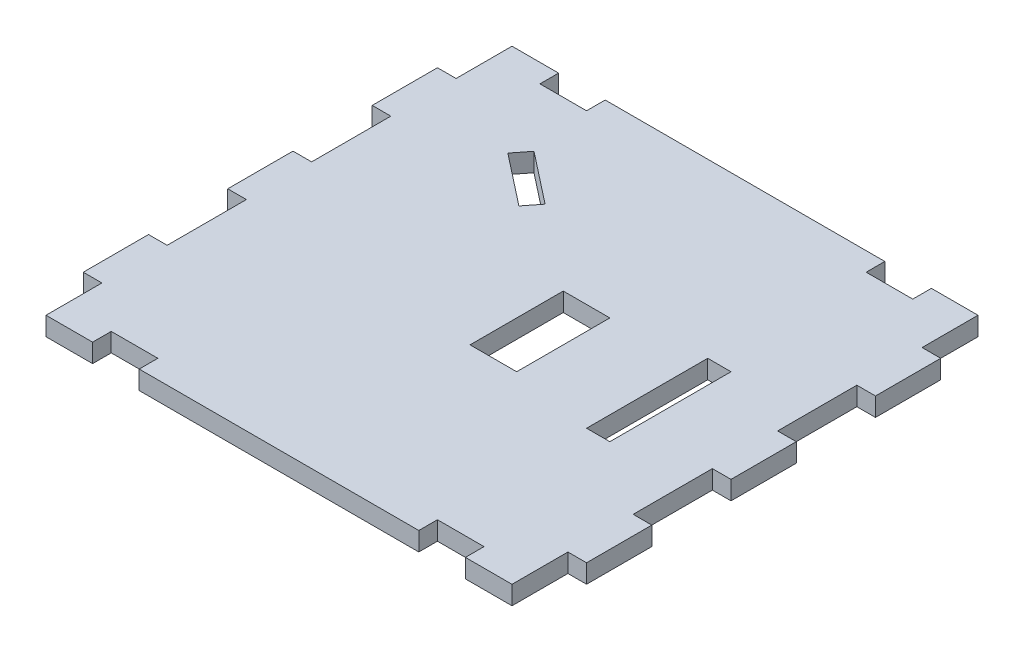
SolidWorks part; units mm, degrees
ref_plane "Front Plane" through (0, 0, 0) normal (0, 0, 1) x (1, 0, 0)
ref_plane "Top Plane" through (0, 0, 0) normal (0, 1, 0) x (1, 0, 0)
ref_plane "Right Plane" through (0, 0, 0) normal (1, 0, 0) x (0, 0, -1)
sketch "Sketch1" plane through (0, 0, 0) normal (0, 1, 0) x (1, 0, 0)
  line L1 (-25, 25) -> (25, 25)
  line L2 (-25, 25) -> (-25, -25)
  line L3 (-25, -25) -> (25, -25)
  line L4 (25, 25) -> (25, -25)
  line L5 (-25, 25) -> (25, -25) construction
  line L6 (-25, -25) -> (25, 25) construction
  line L7 (25, -19) -> (27, -19)
  line L8 (25, -19) -> (25, -12)
  line L9 (25, -12) -> (27, -12)
  line L10 (27, -19) -> (27, -12)
  line L11 (25, -3.5) -> (27, -3.5)
  line L12 (25, -3.5) -> (25, 3.5)
  line L13 (25, 3.5) -> (27, 3.5)
  line L14 (27, -3.5) -> (27, 3.5)
  line L15 (25, 12) -> (27, 12)
  line L16 (25, 12) -> (25, 19)
  line L17 (25, 19) -> (27, 19)
  line L18 (27, 12) -> (27, 19)
  line L19 (14.5, 6.5) -> (17, 6.5)
  line L20 (14.5, 6.5) -> (14.5, -6.5)
  line L21 (14.5, -6.5) -> (17, -6.5)
  line L22 (17, 6.5) -> (17, -6.5)
  line L23 (-25, 19) -> (-27, 19)
  line L24 (-25, 19) -> (-25, 12)
  line L25 (-25, 12) -> (-27, 12)
  line L26 (-27, 19) -> (-27, 12)
  line L27 (-25, 3.5) -> (-27, 3.5)
  line L28 (-25, 3.5) -> (-25, -3.5)
  line L29 (-25, -3.5) -> (-27, -3.5)
  line L30 (-27, 3.5) -> (-27, -3.5)
  line L31 (-25, -12) -> (-27, -12)
  line L32 (-25, -12) -> (-25, -19)
  line L33 (-25, -19) -> (-27, -19)
  line L34 (-27, -12) -> (-27, -19)
  point P0 (0, 0)
  dimension "D1" = 50
  dimension "D2" = 50
  dimension "D3" = 2
  dimension "D4" = 2
  dimension "D5" = 2
  dimension "D6" = 7
  dimension "D7" = 7
  dimension "D8" = 7
  dimension "D9" = 6
  dimension "D10" = 8.5
  dimension "D11" = 8.5
  dimension "D12" = 6
  dimension "D13" = 2.5
  dimension "D14" = 13
  dimension "D15" = 18.5
  dimension "D16" = 18.5
  dimension "D17" = 8
  dimension "D18" = 7
  dimension "D19" = 7
  dimension "D20" = 7
  dimension "D21" = 2
  dimension "D22" = 2
  dimension "D23" = 2
  dimension "D24" = 8.5
  dimension "D25" = 8.5
  dimension "D26" = 6
  dimension "D27" = 6
extrude "Boss-Extrude1" add sketch "Sketch1" along normal blind 2 contours L4 L1 L2 L3 L19 L22 L21 L20 | L11 L14 L13 L4 | L15 L18 L17 L4 | L7 L10 L9 L4 | L27 L30 L29 L2 | L31 L34 L33 L2 | L26 L25 L24 L23
sketch "Sketch3" plane through (0, 2, 0) normal (0, 1, 0) x (1, 0, 0)
  line L0 (-25, 25) -> (25, 25) construction
  line L1 (15, 25) -> (20, 25)
  line L2 (15, 25) -> (15, 23)
  line L3 (15, 23) -> (20, 23)
  line L4 (20, 25) -> (20, 23)
  line L5 (25, 25) -> (25, 19) construction
  line L6 (-25, -25) -> (25, -25) construction
  line L7 (15, -25) -> (20, -25)
  line L8 (15, -25) -> (15, -23)
  line L9 (15, -23) -> (20, -23)
  line L10 (20, -25) -> (20, -23)
  line L11 (25, -19) -> (25, -25) construction
  line L12 (-25, 25) -> (25, 25) construction
  line L13 (-15, 25) -> (-20, 25)
  line L14 (-15, 25) -> (-15, 23)
  line L15 (-15, 23) -> (-20, 23)
  line L16 (-20, 25) -> (-20, 23)
  line L17 (-25, -25) -> (25, -25) construction
  line L18 (-15, -25) -> (-20, -25)
  line L19 (-15, -25) -> (-15, -23)
  line L20 (-15, -23) -> (-20, -23)
  line L21 (-20, -25) -> (-20, -23)
  line L22 (-25, -19) -> (-25, -25) construction
  line L23 (-25, 25) -> (-25, 19) construction
  dimension "D1" = 5
  dimension "D2" = 2
  dimension "D3" = 5
  dimension "D4" = 2
  dimension "D5" = 5
  dimension "D6" = 5
  dimension "D7" = 5
  dimension "D8" = 5
  dimension "D9" = 2
  dimension "D10" = 2
  dimension "D11" = 5
  dimension "D12" = 5
extrude "Cut-Extrude1" cut sketch "Sketch3" against normal blind 2
sketch "Sketch4" plane through (0, 2, 0) normal (0, 1, 0) x (1, 0, 0)
  line L0 (-25, -25) -> (-20, -25) construction
  line L1 (5.5, 5) -> (0.5, 5)
  line L2 (5.5, 5) -> (5.5, -5)
  line L3 (5.5, -5) -> (0.5, -5)
  line L4 (0.5, 5) -> (0.5, -5)
  line L5 (5.5, 5) -> (0.5, -5) construction
  line L6 (5.5, -5) -> (0.5, 5) construction
  line L7 (-25, 25) -> (-20, 25) construction
  line L9 (14.5, 6.5) -> (14.5, -6.5) construction
  point P0 (3, 0)
  dimension "D1" = 10
  dimension "D2" = 5
  dimension "D3" = 20
  dimension "D4" = 20
  dimension "D5" = 9
extrude "Cut-Extrude2" cut sketch "Sketch4" against normal blind 2
sketch "Sketch5" plane through (0, 2, 0) normal (0, 1, 0) x (1, 0, 0)
  line L0 (-25, 25) -> (0.5, 5) construction
  line L1 (-14.0568, 16.4171) -> (-8.5488, 12.0971)
  line L2 (-14.0568, 16.4171) -> (-15.2911, 14.8434)
  line L3 (-8.5488, 12.0971) -> (-9.7831, 10.5234)
  line L4 (-15.2911, 14.8434) -> (-9.7831, 10.5234)
  dimension "D1" = 2
  dimension "D2" = 7
  dimension "D3" = 11.5
  dimension "D4" = 13.9076
extrude "Cut-Extrude3" cut sketch "Sketch5" against normal blind 2
